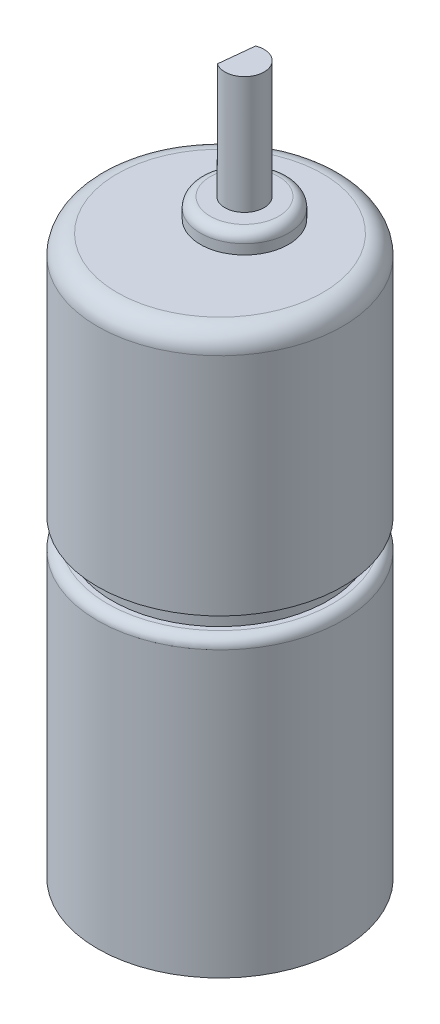
SolidWorks part; units mm, degrees
ref_plane "Front Plane" through (0, 0, 0) normal (0, 0, 1) x (1, 0, 0)
ref_plane "Top Plane" through (0, 0, 0) normal (0, 1, 0) x (1, 0, 0)
ref_plane "Right Plane" through (0, 0, 0) normal (1, 0, 0) x (0, 0, -1)
sketch "Sketch1" plane through (0, 0, 0) normal (0, 1, 0) x (1, 0, 0)
  circle A0 centre (0, 0) radius 12.5
  point P2 (0, 0)
  dimension "D1" = 25
extrude "Boss-Extrude1" add sketch "Sketch1" along normal blind 25
sketch "Sketch2" plane through (0, 0, 0) normal (0, -1, 0) x (1, 0, 0)
  circle A0 centre (0, 0) radius 11
  dimension "D1" = 22
extrude "Boss-Extrude2" add sketch "Sketch2" along normal blind 2
sketch "Sketch3" plane through (0, -2, 0) normal (0, -1, 0) x (1, 0, 0)
  circle A0 centre (0, 0) radius 12.5
  point P3 (0, 0)
extrude "Boss-Extrude3" add sketch "Sketch3" along normal blind 30
sketch "Sketch4" plane through (0, 25, 0) normal (0, -1, 0) x (1, 0, 0)
  circle A0 centre (0, -2.5) radius 4.5
  point P3 (0, 0)
  point P4 (-0.6683, -4.0802)
  point P5 (0, -3.5174)
  dimension "D1" = 9
  dimension "D2" = 2.5
extrude "Boss-Extrude4" add sketch "Sketch4" against normal blind 2
fillet "Fillet1" radius 2 1 edges at (0, 25, 12.5)
fillet "Fillet2" radius 1 1 edges at (0, -2, -12.5)
fillet "Fillet3" radius 1 1 edges at (0, 27, -7)
sketch "Sketch5" plane through (0, 27, 0) normal (0, 1, 0) x (1, 0, 0)
  circle A0 centre (0, 2.5) radius 2
  dimension "D1" = 4
extrude "Boss-Extrude5" add sketch "Sketch5" along normal blind 12
sketch "Sketch10" plane through (0, 39, 0) normal (0, 1, 0) x (1, 0, 0)
  line L0 (-0.7315, 4.3614) -> (-1.1037, 0.8321)
  circle A0 centre (0, 2.5) radius 2 construction
  arc A2 (-0.7315, 4.3614) -> (-1.1037, 0.8321) centre (0, 2.5) ccw
extrude "Cut-Extrude1" cut sketch "Sketch10" against normal blind 9
